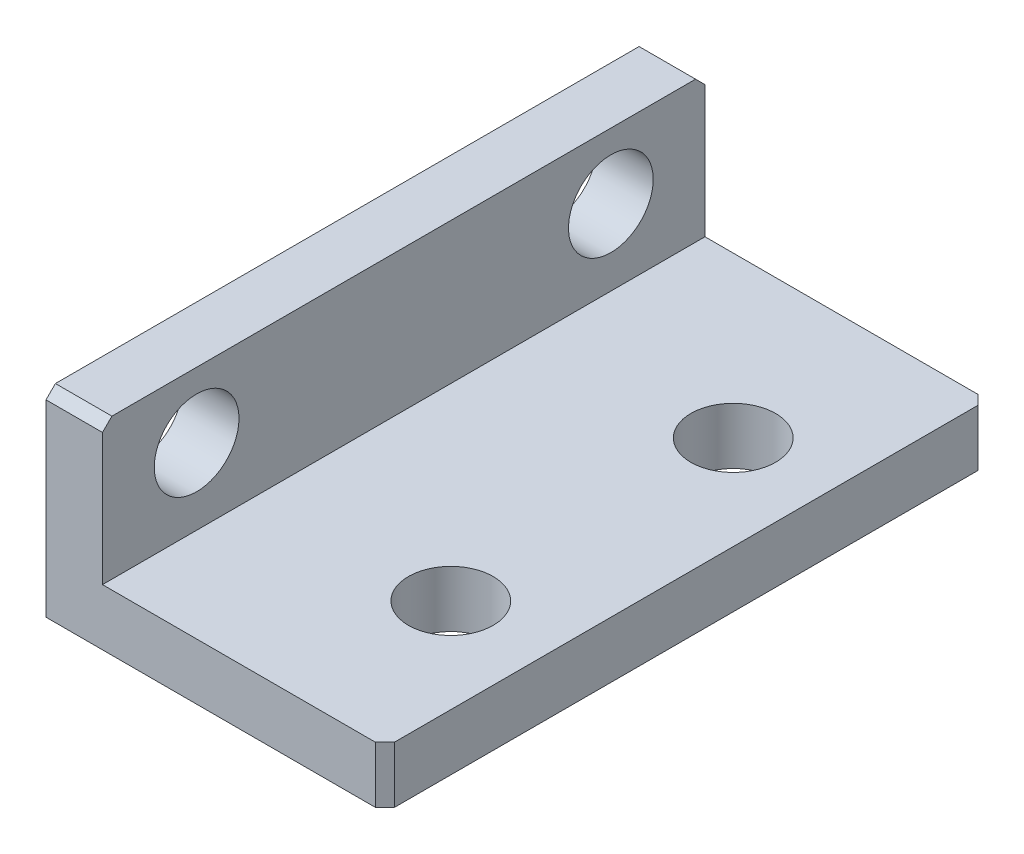
SolidWorks part; units mm, degrees
material "2014 合金"
ref_plane "前视基准面" through (0, 0, 0) normal (0, 0, 1) x (1, 0, 0)
ref_plane "上视基准面" through (0, 0, 0) normal (0, 1, 0) x (1, 0, 0)
ref_plane "右视基准面" through (0, 0, 0) normal (1, 0, 0) x (0, 0, -1)
sketch "草图6" plane through (0, 0, 0) normal (0, 0, 1) x (1, 0, 0)
  line L0 (0, 0) -> (0, 7.5)
  line L1 (0, 0) -> (15, 0)
  dimension "D1" = 7.5
  dimension "D2" = 15
extrude "拉伸-薄壁1" add sketch "草图6" along normal mid plane 32 thin thin type one direction wall 3
hole_wizard "Ø4.5 (4.5) 直径孔1" positions "草图7" profile "草图8" hole size "Ø4.5" standard "Gb"
sketch "草图7" plane through (0, -1.729, -9.85) normal (1, 0, 0) x (0, 0, 1)
  point P0 (-1.15, -5.75)
  point P3 (20.85, -5.75)
sketch "草图8" plane through (0, 4.021, -11) normal (0, 1, 0) x (0, 0, -1)
  line L0 (0, 0) -> (0, 6.3519)
  line L1 (0, 6.3519) -> (2.25, 5)
  line L2 (2.25, 5) -> (2.25, 0)
  line L3 (2.25, 0) -> (0, 0)
  line L4 (0, 6.3519) -> (-2.25, 5) construction
  line L5 (0, -6.35) -> (0, 107.95) construction
  dimension "孔直径" = 4.5
  dimension "孔深度" = 5
  dimension "导头角度" = 118
hole_wizard "Ø4.5 (4.5) 直径孔2" positions "草图10" profile "草图9" hole size "Ø4.5" standard "Gb"
sketch "草图10" plane through (0, 0, 0) normal (0, 1, 0) x (1, 0, 0)
  line L0 (0, 0) -> (13.1675, 0) construction
  line L3 (10, 7.5) -> (10, -7.5) construction
  line L6 (15, -16) -> (15, 16) construction
  point P0 (10, -7.5)
  point P2 (10, 7.5)
  dimension "D1" = 5
  dimension "D2" = 15
sketch "草图9" plane through (10, 0, 7.5) normal (1, 0, 0) x (0, 0, 1)
  line L0 (0, 0) -> (0, 6.3519)
  line L1 (0, 6.3519) -> (2.25, 5)
  line L2 (2.25, 5) -> (2.25, 0)
  line L5 (2.25, 0) -> (0, 0)
  line L10 (0, 6.3519) -> (-2.25, 5) construction
  line L11 (0, -6.35) -> (0, 107.95) construction
  dimension "孔直径" = 4.5
  dimension "孔深度" = 5
  dimension "导头角度" = 118
chamfer "倒角1" distance 0.5 angle 45 4 edges at (15, -1.5, -16) (15, -1.5, 16) (-1.5, 7.5, -16) (-1.5, 7.5, 16)
